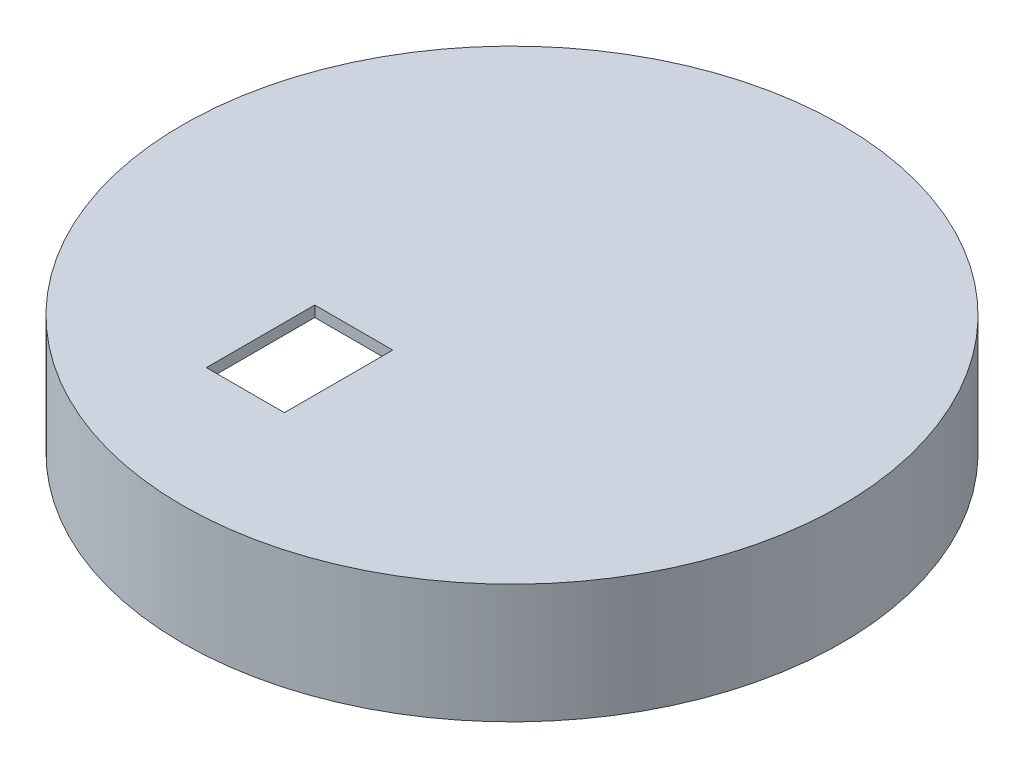
SolidWorks part; units mm, degrees
ref_plane "Ebene vorne" through (0, 0, 0) normal (0, 0, 1) x (1, 0, 0)
ref_plane "Ebene oben" through (0, 0, 0) normal (0, 1, 0) x (1, 0, 0)
ref_plane "Ebene rechts" through (0, 0, 0) normal (1, 0, 0) x (0, 0, -1)
sketch "Skizze1" plane through (0, 0, 0) normal (0, 1, 0) x (1, 0, 0)
  circle A0 centre (0, 0) radius 30.405
  circle A1 centre (0, 0) radius 28.405
  dimension "D1" = 60.81
  dimension "D2" = 2
extrude "Aufsatz-Linear austragen1" add sketch "Skizze1" along normal blind 10
sketch "Skizze2" plane through (0, 10, 0) normal (0, 1, 0) x (1, 0, 0)
  circle A0 centre (0, 0) radius 30.405
  circle A1 centre (0, 0) radius 30.405 construction
extrude "Aufsatz-Linear austragen2" add sketch "Skizze2" along normal blind 1
sketch "Skizze3" plane through (0, 11, 0) normal (0, 1, 0) x (1, 0, 0)
  line L0 (0, 0) -> (-46.4213, 0) construction
  line L1 (-30.405, 0) -> (-30.405, 15.213) construction
  line L2 (0, 0) -> (0, 17.3597) construction
  line L3 (-26.405, 3.75) -> (-30.1729, 3.75)
  line L4 (-26.405, -3.75) -> (-30.1729, -3.75)
  line L5 (26.405, -3.75) -> (30.1729, -3.75)
  line L6 (26.405, 3.75) -> (30.1729, 3.75)
  line L7 (-30.1729, 3.75) -> (-34.1632, 0.7281)
  line L8 (-34.1632, 0.7281) -> (-30.1729, -3.75)
  line L9 (34.1632, 0.7281) -> (30.1729, -3.75)
  line L10 (30.1729, 3.75) -> (34.1632, 0.7281)
  circle A0 centre (-26.405, 0) radius 2.75
  circle A2 centre (0, 0) radius 30.405 construction
  circle A3 centre (26.405, 0) radius 2.75
  arc A4 (-26.405, 3.75) -> (-26.405, -3.75) centre (-26.405, 0) cw
  arc A5 (26.405, 3.75) -> (26.405, -3.75) centre (26.405, 0) ccw
  circle M8 centre (0, 0) radius 30.405
  dimension "D1" = 5.5
  dimension "D3" = 1
  dimension "D2" = 4
extrude "Schnitt-Linear austragen1" [suppressed] cut sketch "Skizze3" against normal through all contours A0 | A4 L3 L4 A0 M8 | L7 L8 M8 | A3 | L6 A5 L5 A3 M8 | L10 L9 M8
sketch "Skizze4" plane through (0, 10, 0) normal (0, -1, 0) x (1, 0, 0)
  line L0 (0, 0) -> (39.4101, 0) construction
  line L1 (30.405, 0) -> (30.405, 9.5037) construction
  line L2 (0, 0) -> (0, 10.4457) construction
  circle A0 centre (0, 0) radius 30.405 construction
  circle A1 centre (27.605, 0) radius 1.5 construction
  arc A2 (28.1268, 3.9658) -> (28.1268, -3.9658) centre (27.605, 0) ccw
  circle A3 centre (0, 0) radius 28.405 construction
  arc A4 (-28.1268, 3.9658) -> (-28.1268, -3.9658) centre (-27.605, 0) cw
  circle M4 centre (0, 0) radius 28.405
  dimension "D1" = 3
  dimension "D3" = 2.5
  dimension "D2" = 2.8
extrude "Aufsatz-Linear austragen3" add sketch "Skizze4" along normal up to surface (10 mm away) contours A4 M4 | A2 M4 up to face at (0, 0, 30.405)
sketch "Skizze5" plane through (0, 0, 0) normal (0, -1, 0) x (1, 0, 0)
  line L0 (0, 0) -> (40.9284, 0)
  line L1 (30.405, 0) -> (30.405, 7.0978) construction
  line L2 (0, 0) -> (0, 11.2853)
  circle A0 centre (27.605, 0) radius 1.5
  circle A1 centre (0, 0) radius 30.405 construction
  circle A2 centre (-27.605, 0) radius 1.5
  dimension "D1" = 3
  dimension "D2" = 2.8
extrude "Schnitt-Linear austragen2" cut sketch "Skizze5" against normal blind 10 contours A2 | L0 A0 | L0 A0
sketch "Skizze6" plane through (0, 11, 0) normal (0, 1, 0) x (1, 0, 0)
  line L1 (-9.9081, -18.2886) -> (-2.7081, -18.2886)
  line L2 (-9.9081, -18.2886) -> (-9.9081, -8.2886)
  line L3 (-9.9081, -8.2886) -> (-2.7081, -8.2886)
  line L4 (-2.7081, -18.2886) -> (-2.7081, -8.2886)
  line L5 (-9.9081, -18.2886) -> (-2.7081, -8.2886) construction
  line L6 (-9.9081, -8.2886) -> (-2.7081, -18.2886) construction
  point P0 (-6.3081, -13.2886)
  dimension "D1" = 10
  dimension "D2" = 7.2
extrude "Schnitt-Linear austragen3" cut sketch "Skizze6" against normal blind 10
pattern_circular "Kreismuster1" count 2 every 90 about axis through (0, 0, 0) along (0, 1, 0) of "Aufsatz-Linear austragen3", "Schnitt-Linear austragen2"
